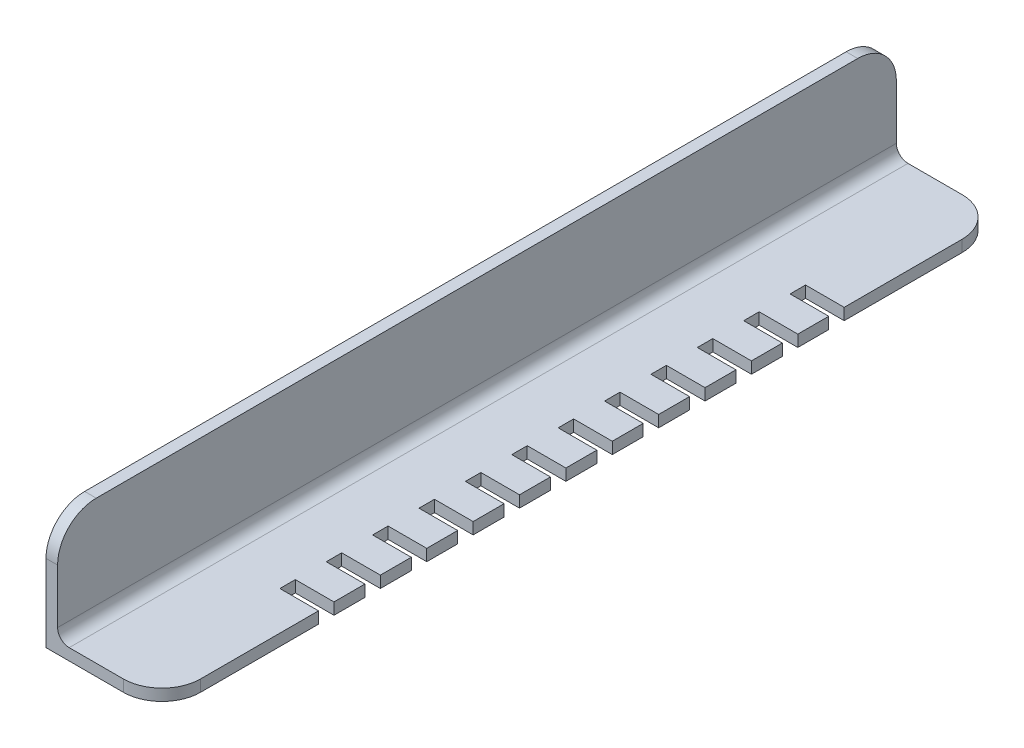
SolidWorks part; units mm, degrees
material "AISI 304"
ref_plane "Спереди" through (0, 0, 0) normal (0, 0, 1) x (1, 0, 0)
ref_plane "Сверху" through (0, 0, 0) normal (0, 1, 0) x (1, 0, 0)
ref_plane "Справа" through (0, 0, 0) normal (1, 0, 0) x (0, 0, -1)
sketch "Эскиз1" plane through (0, 0, 0) normal (0, 0, 1) x (1, 0, 0)
  line L0 (0, 0) -> (60, 0)
  line L1 (60, 0) -> (60, 6)
  line L2 (60, 6) -> (6, 6)
  line L3 (6, 6) -> (6, 60)
  line L4 (6, 60) -> (0, 60)
  line L5 (0, 60) -> (0, 0)
  dimension "D1" = 60
  dimension "D2" = 6
extrude "Бобышка-Вытянуть1" add sketch "Эскиз1" along normal mid plane 434
fillet "Скругление1" radius 20 4 edges at (3, 60, -217) (60, 3, -217) (3, 60, 217) (60, 3, 217)
sketch "Эскиз4" plane through (0, 0, 0) normal (0, -1, 0) x (-1, 0, 0)
  line L0 (0, -217) -> (0, 217) construction
  line L1 (-60, -16) -> (-40, -16)
  line L2 (-60, -16) -> (-60, -8)
  line L3 (-60, -8) -> (-40, -8)
  line L4 (-40, -16) -> (-40, -8)
  line L5 (-60, -16) -> (-40, -8) construction
  line L6 (-60, -8) -> (-40, -16) construction
  line L9 (0, -12) -> (-50, -12) construction
  point P0 (-50, -12)
  point P7 (0, 0)
  dimension "D1" = 8
  dimension "D2" = 20
  dimension "D3" = 40
  dimension "D4" = 12
extrude "Вырез-Вытянуть3" cut sketch "Эскиз4" against normal blind 10
pattern_linear "Линейный массив1" count 6 spacing 24 along (0, 0, 1) count 7 spacing 24 along (0, 0, -1) of "Вырез-Вытянуть3"
sketch "Эскиз5" plane through (0, 6, 0) normal (0, 1, 0) x (1, 0, 0)
  line L0 (30, -187) -> (30, 187) construction
  line L1 (0, 0) -> (134.1883, 0) construction
  line L2 (0, -197) -> (0, 197) construction
  line L3 (40, 217) -> (6, 217) construction
  circle A0 centre (30, 187) radius 7.5
  circle A1 centre (30, -187) radius 7.5
  dimension "D1" = 15
  dimension "D2" = 30
  dimension "D3" = 30
extrude "Вырез-Вытянуть4" [suppressed] cut sketch "Эскиз5" against normal blind 10
sketch "Эскиз6" plane through (0, 0, 0) normal (0, -1, 0) x (1, 0, 0)
  line L0 (0, 147) -> (87.786, 147)
  line L1 (0, 217) -> (0, -217) construction
  line L2 (0, -147) -> (93.6009, -147)
  line L3 (0, 217) -> (40, 217) construction
  line L4 (0, -217) -> (40, -217) construction
  dimension "D1" = 70
  dimension "D2" = 70
split line "Разделяющая линия1" [suppressed]
fillet "Скругление2" radius 6 1 edges at (6, 6, 0)
equation "\"D2@Эскиз6\"=\"D1@Эскиз6\""
